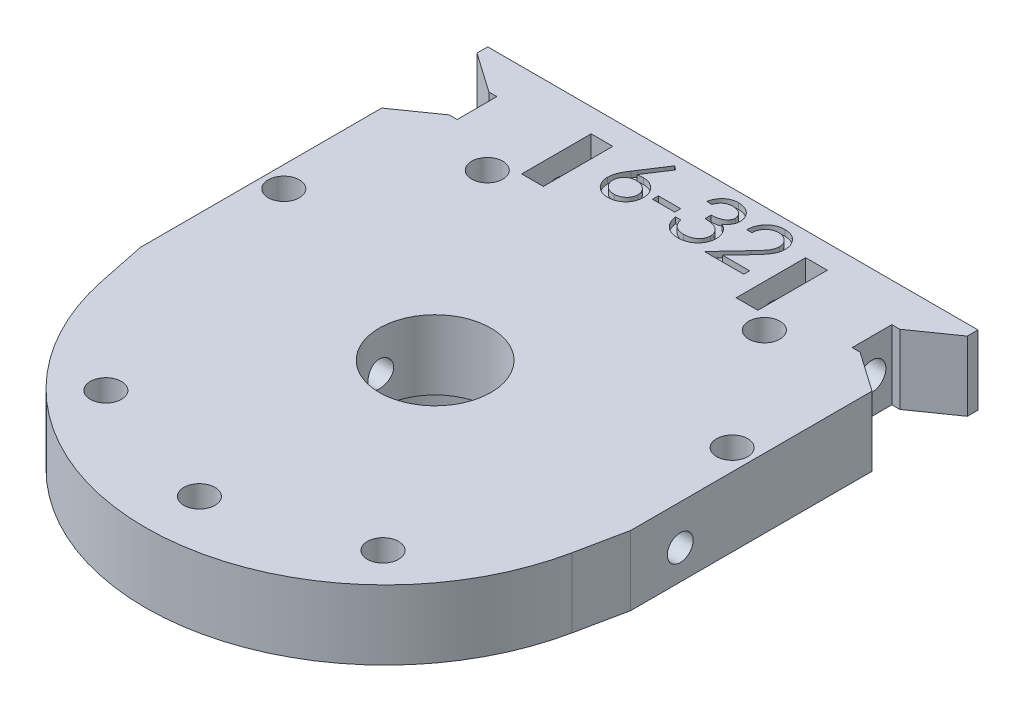
SolidWorks part; units mm, degrees
ref_plane "Front Plane" through (0, 0, 0) normal (0, 0, 1) x (1, 0, 0)
ref_plane "Top Plane" through (0, 0, 0) normal (0, 1, 0) x (1, 0, 0)
ref_plane "Right Plane" through (0, 0, 0) normal (1, 0, 0) x (0, 0, -1)
sketch "Sketch1" plane through (0, 0, 0) normal (0, 1, 0) x (1, 0, 0)
  line L0 (-31.369, 0) -> (-31.369, -44.45)
  line L1 (-31.369, -44.45) -> (-30.0836, -50.6685)
  line L2 (30.0836, -50.6685) -> (31.369, -44.45)
  line L3 (31.369, -44.45) -> (31.369, 0)
  line L4 (31.369, 0) -> (-31.369, 0)
  arc A1 (-30.0836, -50.6685) -> (30.0836, -50.6685) centre (0, -44.45) ccw
  point P11 (0, 0)
  dimension "D3" = 6.35
  dimension "D1" = 62.738
  dimension "D2" = 44.45
extrude "Boss-Extrude1" add sketch "Sketch1" along normal mid plane 8.89
sketch "Sketch2" plane through (0, 4.445, 0) normal (0, 1, 0) x (1, 0, 0)
  line L0 (31.369, 0) -> (-31.369, 0) construction
  circle A0 centre (0, -38.1) radius 7.1438
  dimension "D1" = 14.2875
  dimension "D2" = 38.1
extrude "Cut-Extrude1" cut sketch "Sketch2" against normal through all
sketch "Sketch3" plane through (31.369, 0, 0) normal (1, 0, 0) x (0, 0, -1)
  line L0 (0, 4.445) -> (0, -4.445) construction
  line L1 (-44.45, -4.445) -> (0, -4.445) construction
  circle A0 centre (-7.4676, 0) radius 1.778
  dimension "D1" = 3.556
  dimension "D3" = 4.445
  dimension "D2" = 7.4676
extrude "Cut-Extrude2" cut sketch "Sketch3" against normal blind 25.4
sketch "Sketch7" plane through (0, 4.445, 0) normal (0, 1, 0) x (1, 0, 0)
  line L0 (-31.369, 0) -> (-31.369, -44.45) construction
  line L1 (-31.369, -4.9276) -> (-25.273, -4.9276)
  line L2 (-31.369, -4.9276) -> (-31.369, -10.0076)
  line L3 (-31.369, -10.0076) -> (-25.273, -10.0076)
  line L4 (-25.273, -4.9276) -> (-25.273, -10.0076)
  line L5 (31.369, 0) -> (-31.369, 0) construction
  line L10 (31.369, -44.45) -> (31.369, 0) construction
  line L11 (31.369, -10.0076) -> (25.273, -10.0076)
  line L12 (31.369, -10.0076) -> (31.369, -4.9276)
  line L13 (31.369, -4.9276) -> (25.273, -4.9276)
  line L14 (25.273, -10.0076) -> (25.273, -4.9276)
  dimension "D1" = 6.096
  dimension "D2" = 5.08
  dimension "D3" = 4.9276
extrude "Cut-Extrude12" cut sketch "Sketch7" against normal through all
mirror "Mirror1" about plane through (0, 0, 0) normal (1, 0, 0) of "Cut-Extrude2"
chamfer "Chamfer3" distance 5.08 distance2 3.556 2 edges at (-31.369, 0, 4.9276) (31.369, 0, 10.0076)
chamfer "Chamfer4" distance 3.556 distance2 5.08 2 edges at (31.369, 0, 4.9276) (-31.369, 0, 10.0076)
sketch "Sketch9" plane through (0, 4.445, 0) normal (0, 1, 0) x (1, 0, 0)
  line L0 (-25.273, -4.9276) -> (-25.273, -10.0076) construction
  line L1 (-15.113, -3.0226) -> (-12.3349, -3.0226)
  line L2 (-15.113, -3.0226) -> (-15.113, -11.9126)
  line L3 (-15.113, -11.9126) -> (-12.3349, -11.9126)
  line L4 (-12.3349, -3.0226) -> (-12.3349, -11.9126)
  line L5 (12.3349, -3.0226) -> (15.113, -3.0226)
  line L6 (12.3349, -3.0226) -> (12.3349, -11.9126)
  line L7 (12.3349, -11.9126) -> (15.113, -11.9126)
  line L8 (15.113, -3.0226) -> (15.113, -11.9126)
  line L9 (25.273, -10.0076) -> (25.273, -4.9276) construction
  point P10 (-25.273, -7.4676)
  point P11 (-15.113, -7.4676)
  dimension "D1" = 8.89
  dimension "D2" = 2.7781
  dimension "D3" = 10.16
  dimension "D4" = 10.16
extrude "Cut-Extrude14" cut sketch "Sketch9" against normal up to surface (8.89 mm away) up to face at (0, -4.445, 45.2437)
sketch "Sketch10" plane through (0, 4.445, 0) normal (0, 1, 0) x (1, 0, 0)
  text T0 "6-32" font "Century Gothic" height in points 28
extrude "Cut-Extrude15" cut sketch "Sketch10" against normal blind 0.762
sketch "Sketch12" plane through (0, 4.445, 0) normal (0, 1, 0) x (1, 0, 0)
  circle A0 centre (0, -38.1) radius 30.1625 construction
  circle A7 centre (-17.7291, -62.502) radius 1.9939
  circle A11 centre (0, -68.2625) radius 1.9939
  circle A12 centre (-28.6862, -47.4207) radius 1.9939 [skipped]
  circle A13 centre (-28.6862, -28.7793) radius 1.9939
  circle A14 centre (-17.7291, -13.698) radius 1.9939
  circle A15 centre (0, -7.9375) radius 1.9939 [skipped]
  circle A16 centre (17.7291, -13.698) radius 1.9939
  circle A17 centre (28.6862, -28.7793) radius 1.9939
  circle A18 centre (28.6862, -47.4207) radius 1.9939 [skipped]
  circle A19 centre (17.7291, -62.502) radius 1.9939
  point P24 (0, -38.1)
  dimension "D1" = 60.325
  dimension "D2" = 3.9878
  dimension "D3" = 10
extrude "Cut-Extrude16" cut sketch "Sketch12" against normal through all
sketch "Sketch14" plane through (0, -4.445, 0) normal (0, -1, 0) x (1, 0, 0)
  circle A0 centre (0, 38.1) radius 12.7
  circle A1 centre (0, 38.1) radius 16.51
  circle A2 centre (0, 38.1) radius 7.1438 construction
  dimension "D1" = 25.4
  dimension "D2" = 33.02
extrude "Boss-Extrude3" add sketch "Sketch14" along normal blind 10.16
sketch "Sketch15" plane through (0, 0, 0) normal (1, 0, 0) x (0, 0, -1)
  line L1 (-54.61, -4.445) -> (-54.61, -14.605) construction
  line L2 (-44.45, -4.445) -> (-13.5636, -4.445) construction
  circle A0 centre (-38.1, -0.635) radius 1.651
  dimension "D1" = 3.302
  dimension "D2" = 3.81
  dimension "D3" = 16.51
extrude "Cut-Extrude17" cut sketch "Sketch15" against normal mid plane 127
equation "\"0..0510in\"=0.1"
